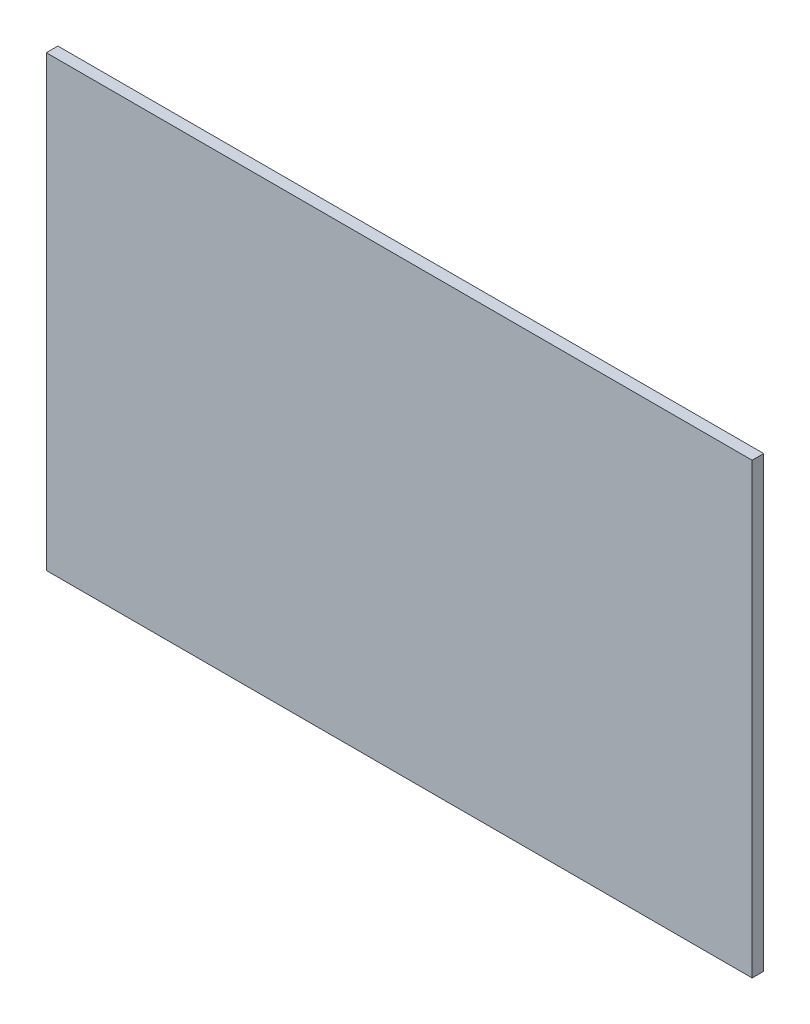
SolidWorks part; units mm, degrees
ref_plane "Front Plane" through (0, 0, 0) normal (0, 0, 1) x (1, 0, 0)
ref_plane "Top Plane" through (0, 0, 0) normal (0, 1, 0) x (1, 0, 0)
ref_plane "Right Plane" through (0, 0, 0) normal (1, 0, 0) x (0, 0, -1)
sketch "Sketch1" plane through (0, 0, 0) normal (0, 0, 1) x (1, 0, 0)
  line L1 (0, 0) -> (2440, 0)
  line L2 (0, 0) -> (0, 1550)
  line L3 (0, 1550) -> (2440, 1550)
  line L4 (2440, 0) -> (2440, 1550)
  dimension "D1" = 2440
  dimension "D2" = 1550
extrude "Boss-Extrude1" add sketch "Sketch1" along normal blind 40
